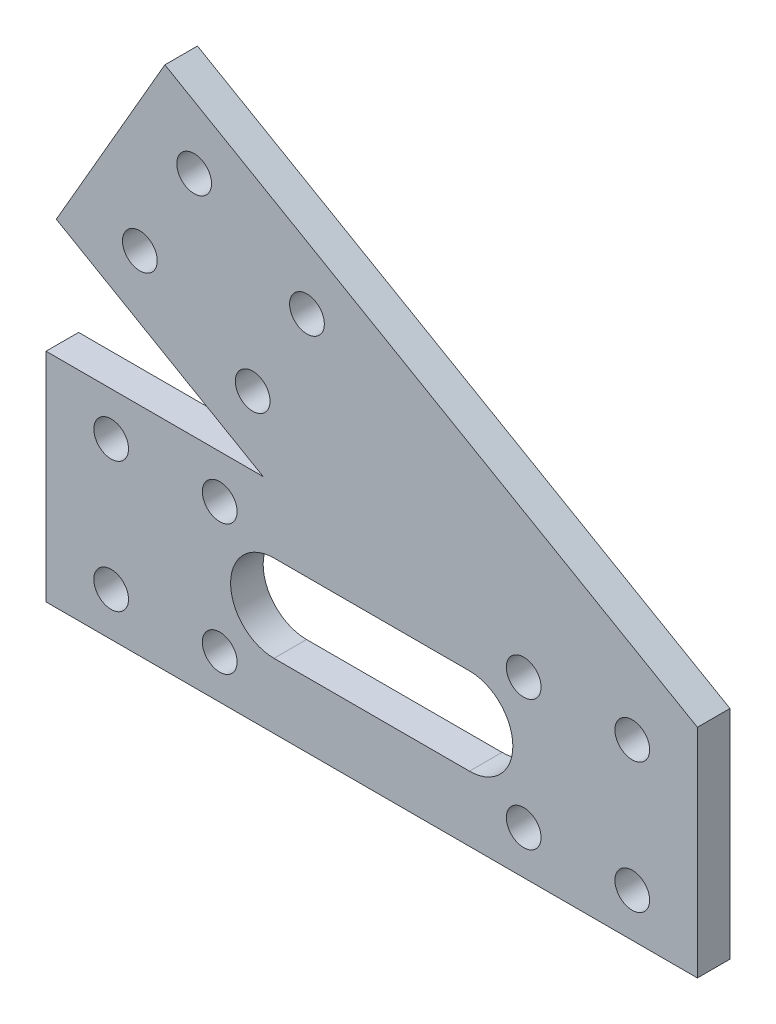
SolidWorks part; units mm, degrees
material "Thornel VCB-20 碳布"
ref_plane "前视基准面" through (0, 0, 0) normal (0, 0, 1) x (1, 0, 0)
ref_plane "上视基准面" through (0, 0, 0) normal (0, 1, 0) x (1, 0, 0)
ref_plane "右视基准面" through (0, 0, 0) normal (1, 0, 0) x (0, 0, -1)
other "Configuration Table"
sketch "草图1" plane through (0, 0, 0) normal (0, 0, 1) x (1, 0, 0)
  line L0 (60, 0) -> (0, 0)
  line L1 (0, 0) -> (0, 20)
  line L2 (0, 20) -> (60, 20) construction
  line L9 (60, 20) -> (60, 0)
  line L11 (20, 20) -> (0.9474, 31)
  line L12 (0.9474, 31) -> (10.9474, 48.3205)
  line L13 (10.9474, 48.3205) -> (60, 20)
  line L14 (20, 20) -> (0, 20)
  dimension "D1" = 20
  dimension "D2" = 60
  dimension "D3" = 150
  dimension "D4" = 30
  dimension "D5" = 20
  dimension "D6" = 22
extrude "凸台-拉伸1" add sketch "草图1" along normal blind 3
sketch "草图2" plane through (0, 0, 3) normal (0, 0, 1) x (1, 0, 0)
  line L0 (13.6436, 40.9904) -> (8.6436, 32.3301) construction
  line L1 (8.6436, 32.3301) -> (29.4282, 20.3301) construction
  line L2 (29.4282, 20.3301) -> (34.4282, 28.9904) construction
  line L3 (34.4282, 28.9904) -> (13.6436, 40.9904) construction
  line L4 (10.9474, 48.3205) -> (0.9474, 31) construction
  line L5 (0.9474, 31) -> (20, 20) construction
  line L6 (60, 20) -> (10.9474, 48.3205) construction
  line L7 (19.0359, 26.3301) -> (24.0359, 34.9904) construction
  line L9 (20, 20) -> (0, 20) construction
  line L10 (6, 16) -> (54, 16) construction
  line L11 (6, 16) -> (6, 4) construction
  line L12 (6, 4) -> (54, 4) construction
  line L13 (54, 16) -> (54, 4) construction
  line L14 (0, 20) -> (0, 0) construction
  line L15 (21, 10) -> (39, 10) construction
  line L16 (21, 14) -> (39, 14)
  line L17 (21, 6) -> (39, 6)
  line L18 (54, 10) -> (39, 10) construction
  line L19 (60, 0) -> (60, 20) construction
  circle A0 centre (13.6436, 40.9904) radius 1.6
  circle A1 centre (8.6436, 32.3301) radius 1.6
  circle A2 centre (24.0359, 34.9904) radius 1.6
  circle A3 centre (19.0359, 26.3301) radius 1.6
  circle A4 centre (29.4282, 20.3301) radius 1.6 construction
  circle A5 centre (34.4282, 28.9904) radius 1.6 construction
  circle A6 centre (6, 16) radius 1.6
  circle A7 centre (6, 4) radius 1.6
  circle A8 centre (54, 16) radius 1.6
  circle A9 centre (54, 4) radius 1.6
  circle A10 centre (16, 16) radius 1.6
  circle A11 centre (16, 4) radius 1.6
  circle A12 centre (44, 16) radius 1.6
  circle A13 centre (44, 4) radius 1.6
  arc A14 (21, 14) -> (21, 6) centre (21, 10) ccw
  arc A15 (39, 6) -> (39, 14) centre (39, 10) ccw
  point P38 (30, 10)
  dimension "D5" = 3.2
  dimension "D10" = 3.2
  dimension "D17" = 4
  dimension "D1" = 10
  dimension "D2" = 5
  dimension "28" = 24
  dimension "D4" = 6
  dimension "D6" = 12
  dimension "D7" = 4
  dimension "D8" = 48
  dimension "D9" = 6
  dimension "D11" = 10
  dimension "D12" = 10
  dimension "D13" = 10
  dimension "D14" = 10
  dimension "D15" = 18
  dimension "D16" = 30
extrude "切除-拉伸1" cut sketch "草图2" against normal blind 10
